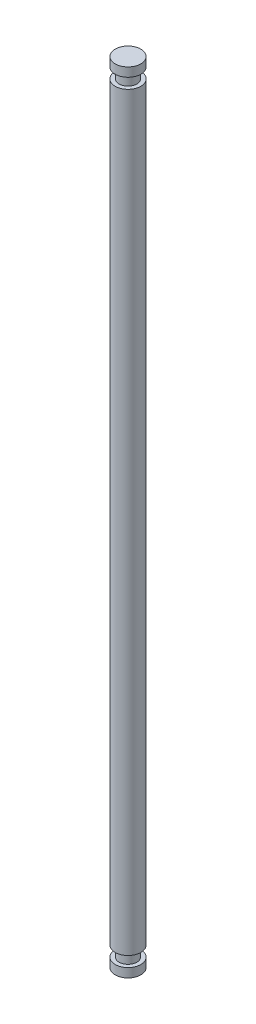
SolidWorks part; units mm, degrees
ref_plane "Front Plane" through (0, 0, 0) normal (1, 0, 0) x (0, 1, 0)
ref_plane "Top Plane" through (0, 0, 0) normal (0, 0, 1) x (0, 1, 0)
ref_plane "Right Plane" through (0, 0, 0) normal (0, 1, 0) x (-1, 0, 0)
sketch "Sketch1" plane through (0, 0, 0) normal (0, 0, 1) x (0, 1, 0)
  line L0 (-976.376, 0) -> (-976.376, 31.7309)
  line L1 (-976.376, 31.7309) -> (-954.024, 31.7309)
  line L2 (-954.024, 31.7309) -> (-954.024, 22.0218)
  line L3 (-954.024, 22.0218) -> (-928.2176, 22.0218)
  line L4 (-928.2176, 22.0218) -> (-928.2176, 31.7309)
  line L5 (-928.2176, 31.7309) -> (928.3446, 31.7309)
  line L6 (928.3446, 31.7309) -> (928.3446, 22.0218)
  line L7 (928.3446, 22.0218) -> (954.151, 22.0218)
  line L8 (954.151, 22.0218) -> (954.151, 31.7309)
  line L9 (954.151, 31.7309) -> (976.376, 31.7309)
  line L10 (976.376, 31.7309) -> (976.376, 0)
  line L11 (976.376, 0) -> (-976.376, 0)
  line L12 (-1001.776, 0) -> (1001.776, 0) construction
  point P14 (0, 0)
  dimension "D1" = 22.225
  dimension "D2" = 48.0314
  dimension "D3" = 1904.5936
  dimension "D4" = 1930.4
  dimension "D5" = 1952.752
  dimension "D6" = 9.7092
  dimension "D7" = 31.7309
revolve "Revolve1" add sketch "Sketch1" angle 360 about L12
sketch "Sketch2" plane through (0, 0, 0) normal (0, 1, 0) x (-1, 0, 0)
  line L1 (24.6062, -6.35) -> (88.0682, -6.35)
  line L2 (24.6062, -6.35) -> (24.6062, 6.35)
  line L3 (24.6062, 6.35) -> (88.0682, 6.35)
  line L4 (88.0682, -6.35) -> (88.0682, 6.35)
  point P2 (0, 0)
  dimension "D1" = 63.4619
  dimension "D2" = 12.7
  dimension "D3" = 88.0682
  dimension "D4" = 6.35
extrude "Cut-Extrude2" cut sketch "Sketch2" along normal blind 1856.5622 from offset 928.2176
